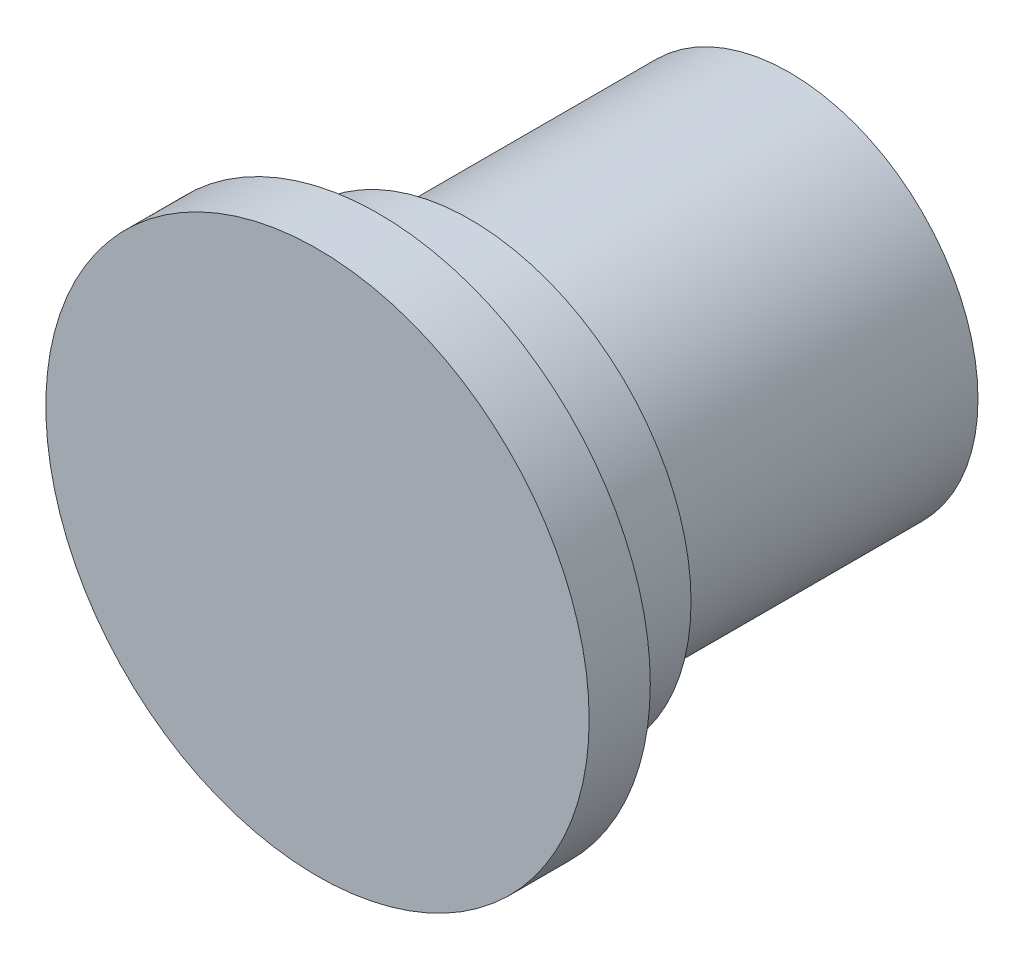
SolidWorks part; units mm, degrees
ref_plane "Front Plane" through (0, 0, 0) normal (0, 0, 1) x (1, 0, 0)
ref_plane "Top Plane" through (0, 0, 0) normal (0, 1, 0) x (1, 0, 0)
ref_plane "Right Plane" through (0, 0, 0) normal (1, 0, 0) x (0, 0, -1)
sketch "Sketch1" plane through (0, 0, 0) normal (0, 0, 1) x (1, 0, 0)
  circle A0 centre (0, 0) radius 8
  dimension "D1" = 16
extrude "Boss-Extrude1" add sketch "Sketch1" against normal blind 1.8
sketch "Sketch2" plane through (0, 0, -1.8) normal (0, 0, -1) x (-1, 0, 0)
  circle A0 centre (0, 0) radius 6.5
  dimension "D1" = 13
extrude "Boss-Extrude2" add sketch "Sketch2" along normal blind 2.7
sketch "Sketch3" plane through (0, 0, -4.5) normal (0, 0, -1) x (-1, 0, 0)
  circle A0 centre (0, 0) radius 5.55
  dimension "D1" = 11.1
extrude "Boss-Extrude3" add sketch "Sketch3" along normal blind 9.4
